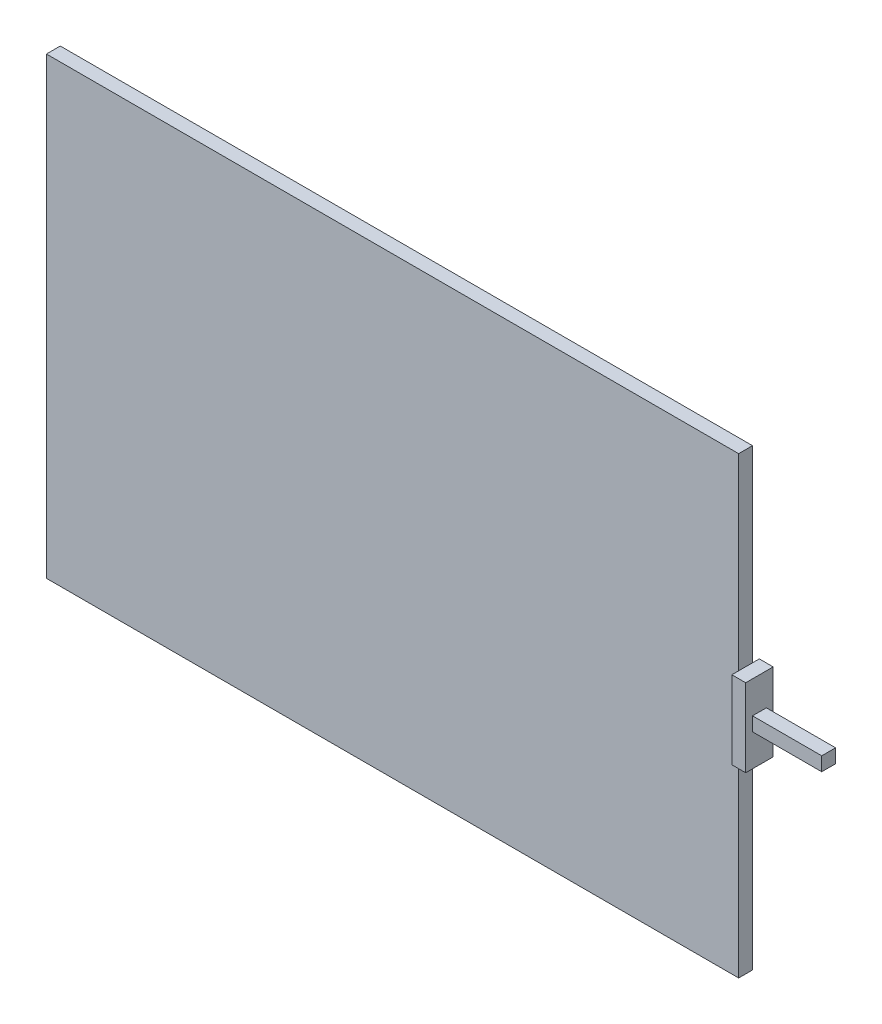
SolidWorks part; units mm, degrees
ref_plane "Front Plane" through (0, 0, 0) normal (0, 0, 1) x (1, 0, 0)
ref_plane "Top Plane" through (0, 0, 0) normal (0, 1, 0) x (1, 0, 0)
ref_plane "Right Plane" through (0, 0, 0) normal (1, 0, 0) x (0, 0, -1)
sketch "Sketch1" plane through (0, 0, 0) normal (0, 0, 1) x (1, 0, 0)
  line L1 (-50, 32.8) -> (50, 32.8)
  line L2 (-50, 32.8) -> (-50, -32.8)
  line L3 (-50, -32.8) -> (50, -32.8)
  line L4 (50, 32.8) -> (50, -32.8)
  line L5 (-50, 32.8) -> (50, -32.8) construction
  line L6 (-50, -32.8) -> (50, 32.8) construction
  point P0 (0, 0)
  dimension "D1" = 100
  dimension "D2" = 65.6
extrude "Boss-Extrude1" add sketch "Sketch1" along normal blind 2 contours L2 L1 L4 L3
sketch "Sketch2" plane through (50, 0, 0) normal (1, 0, 0) x (0, 0, -1)
  line L0 (-1, 32.8) -> (-1, -32.8) construction
  line L1 (-2, 32.8) -> (0, 32.8) construction
  line L2 (-2, -32.8) -> (0, -32.8) construction
  line L3 (-2, 0) -> (0, 0) construction
  line L4 (-2, 32.8) -> (-2, -32.8) construction
  line L6 (-2.9841, 5.6307) -> (0.9841, 5.6307)
  line L7 (-2.9841, 5.6307) -> (-2.9841, -5.6307)
  line L8 (-2.9841, -5.6307) -> (0.9841, -5.6307)
  line L9 (0.9841, 5.6307) -> (0.9841, -5.6307)
  line L10 (-2.9841, 5.6307) -> (0.9841, -5.6307) construction
  line L11 (-2.9841, -5.6307) -> (0.9841, 5.6307) construction
  point P11 (-1, 0)
extrude "Boss-Extrude2" add sketch "Sketch2" along normal blind 2
sketch "Sketch3" plane through (52, 0, 0) normal (1, 0, 0) x (0, 0, -1)
  line L0 (0.9841, 0) -> (-2.9841, 0) construction
  line L1 (0.9841, -5.6307) -> (0.9841, 5.6307) construction
  line L2 (-2.9841, 5.6307) -> (-2.9841, -5.6307) construction
  line L4 (-2, 1) -> (0, 1)
  line L5 (-2, 1) -> (-2, -1)
  line L6 (-2, -1) -> (0, -1)
  line L7 (0, 1) -> (0, -1)
  line L8 (-2, 1) -> (0, -1) construction
  line L9 (-2, -1) -> (0, 1) construction
  point P6 (-1, 0)
  dimension "D1" = 2
  dimension "D2" = 2
extrude "Boss-Extrude3" add sketch "Sketch3" along normal blind 10
